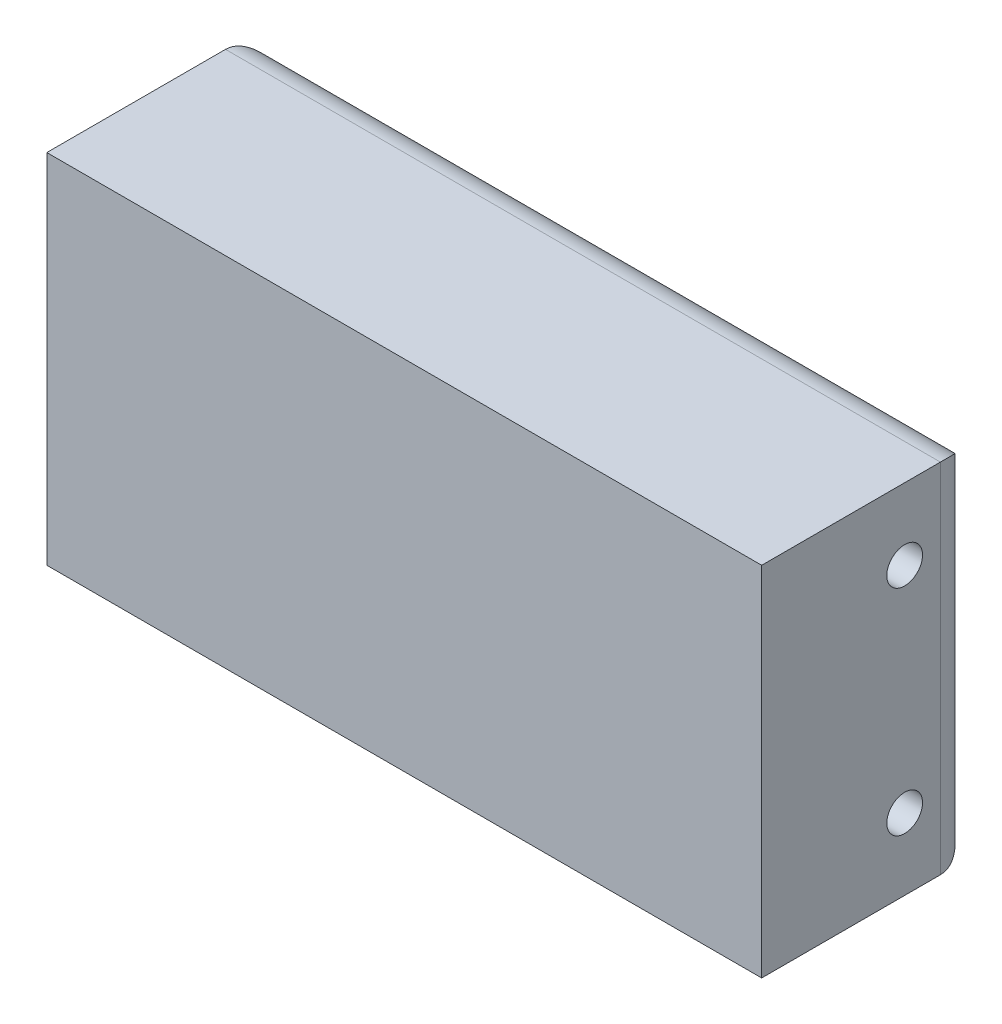
SolidWorks part; units mm, degrees
ref_plane "Front Plane" through (0, 0, 0) normal (0, 0, 1) x (1, 0, 0)
ref_plane "Top Plane" through (0, 0, 0) normal (0, 1, 0) x (1, 0, 0)
ref_plane "Right Plane" through (0, 0, 0) normal (1, 0, 0) x (0, 0, -1)
sketch "Sketch1" plane through (0, 0, 0) normal (0, 0, 1) x (1, 0, 0)
  line L1 (-50, 25) -> (50, 25)
  line L2 (-50, 25) -> (-50, -25)
  line L3 (-50, -25) -> (50, -25)
  line L4 (50, 25) -> (50, -25)
  line L5 (-50, 25) -> (50, -25) construction
  line L6 (-50, -25) -> (50, 25) construction
  point P0 (0, 0)
  dimension "D1" = 50
  dimension "D2" = 100
extrude "Boss-Extrude1" add sketch "Sketch1" along normal blind 30
sketch "Sketch2" plane through (50, 0, 0) normal (1, 0, 0) x (0, 0, -1)
  line L0 (-30, 25) -> (0, 25) construction
  line L1 (-30, -25) -> (-30, 25) construction
  circle A0 centre (-10, 15) radius 2.5
  circle A1 centre (-10, -15) radius 2.5
  dimension "D1" = 5
  dimension "D2" = 5
  dimension "D3" = 30
  dimension "D4" = 10
  dimension "D5" = 20
  dimension "D6" = 20
extrude "Cut-Extrude1" cut sketch "Sketch2" against normal through all
fillet "Fillet1" radius 5 4 edges at (50, 0, 0) (0, -25, 0) (-50, 0, 0) (0, 25, 0)
sketch "Sketch3" plane through (0, 0, 0) normal (0, 0, -1) x (-1, 0, 0)
  line L0 (-50, 25) -> (50, 25) construction
  line L1 (-50, -25) -> (-50, 25) construction
  line L2 (50, 25) -> (50, -25) construction
  circle A0 centre (-30, 15) radius 2.5
  circle A1 centre (30, 15) radius 2.5
  circle A2 centre (0, 15) radius 2.5
  dimension "D1" = 5
  dimension "D2" = 5
  dimension "D5" = 5
  dimension "D3" = 10
  dimension "D4" = 10
  dimension "D6" = 10
  dimension "D7" = 20
  dimension "D8" = 20
  dimension "D9" = 30
extrude "Cut-Extrude2" cut sketch "Sketch3" against normal up to surface (7.5 mm away)
